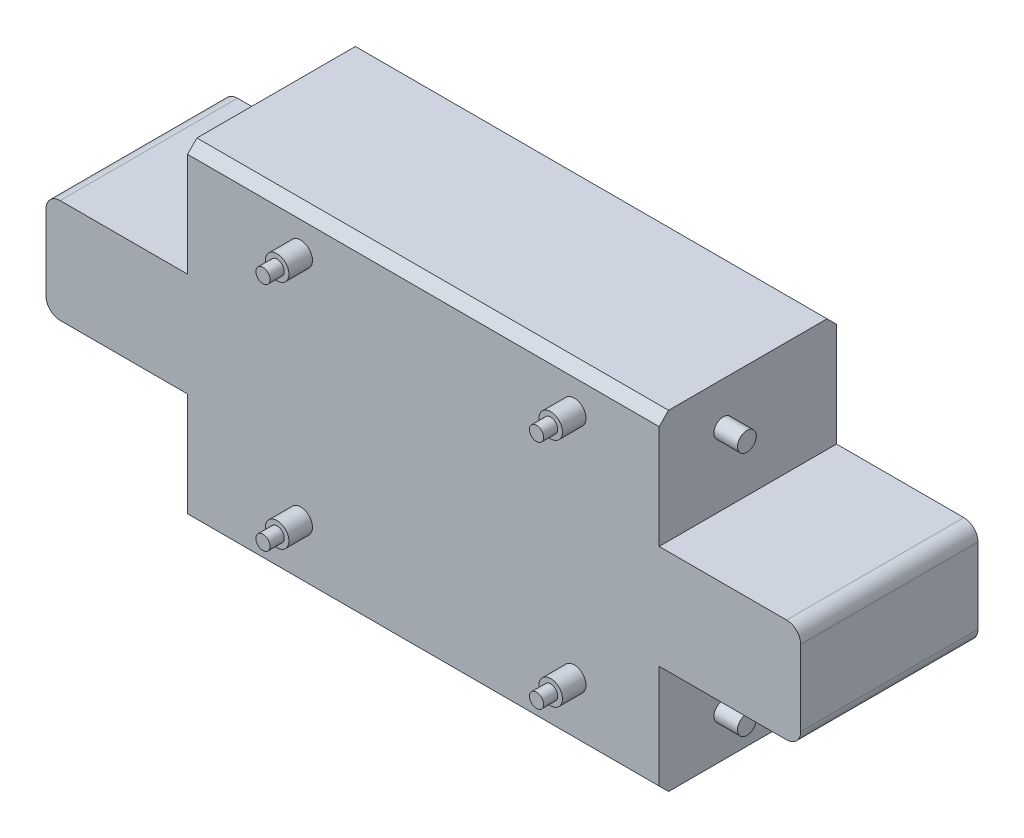
SolidWorks part; units mm, degrees
ref_plane "Alzado" through (0, 0, 0) normal (0, 0, 1) x (1, 0, 0)
ref_plane "Planta" through (0, 0, 0) normal (0, 1, 0) x (1, 0, 0)
ref_plane "Vista lateral" through (0, 0, 0) normal (1, 0, 0) x (0, 0, -1)
sketch "Croquis1" plane through (0, 0, 0) normal (0, 0, 1) x (1, 0, 0)
  line L0 (-62.5244, 0.3719) -> (-62.5244, -23.6281)
  line L5 (-62.5244, 46.3719) -> (37.4756, 46.3719)
  line L6 (-62.5244, 46.3719) -> (-62.5244, 22.3719)
  line L7 (-62.5244, -23.6281) -> (37.4756, -23.6281)
  line L8 (37.4756, 46.3719) -> (37.4756, 22.3719)
  line L9 (-62.5244, 22.3719) -> (-92.5244, 22.3719)
  line L11 (-62.5244, 0.3719) -> (-92.5244, 0.3719)
  line L12 (-92.5244, 22.3719) -> (-92.5244, 0.3719)
  line L13 (37.4756, 22.3719) -> (67.4756, 22.3719)
  line L15 (37.4756, 0.3719) -> (67.4756, 0.3719)
  line L16 (67.4756, 22.3719) -> (67.4756, 0.3719)
  line L17 (37.4756, 0.3719) -> (37.4756, -23.6281)
  point P12 (-12.5244, -23.6281)
  dimension "D1" = 160
  dimension "D2" = 22
  dimension "D3" = 70
  dimension "D4" = 24
  dimension "D5" = 24
  dimension "D6" = 22
  dimension "D7" = 100
  dimension "D8" = 80
  dimension "D9" = 30
extrude "Saliente-Extruir1" add sketch "Croquis1" along normal blind 37.6
sketch "Croquis2" plane through (-62.5244, 0, 0) normal (-1, 0, 0) x (0, 0, 1)
  line L2 (0, 0.3719) -> (0, -23.6281) construction
  line L3 (37.6, -23.6281) -> (0, -23.6281) construction
  line L4 (0, 46.3719) -> (0, 22.3719) construction
  line L5 (37.6, 46.3719) -> (0, 46.3719) construction
  circle A0 centre (24, -14.6281) radius 2
  circle A1 centre (24, 37.3719) radius 2
  dimension "D3" = 4
  dimension "D4" = 4
  dimension "D1" = 24
  dimension "D2" = 9
  dimension "D5" = 24
  dimension "D6" = 9
extrude "Saliente-Extruir2" add sketch "Croquis2" along normal blind 5 and the other way blind 105
fillet "Redondeo1" radius 3 2 edges at (67.4756, 22.3719, 18.8) (67.4756, 0.3719, 18.8)
chamfer "Chaflán1" distance 2 angle 45 2 edges at (-12.5244, -23.6281, 0) (-12.5244, 46.3719, 0)
chamfer "Chaflán2" distance 2 angle 45 2 edges at (-12.5244, -23.6281, 37.6) (-12.5244, 46.3719, 37.6)
fillet "Redondeo2" radius 3 2 edges at (-92.5244, 22.3719, 18.8) (-92.5244, 0.3719, 18.8)
sketch "Croquis3" plane through (0, 0, 37.6) normal (0, 0, 1) x (1, 0, 0)
  line L0 (67.4756, 3.3719) -> (67.4756, 19.3719) construction
  line L1 (37.4756, 44.3719) -> (-62.5244, 44.3719) construction
  circle A0 centre (-38.5244, 38.1219) radius 2.5
  circle A1 centre (19.4756, 38.1219) radius 2.5
  circle A2 centre (-38.5244, -10.8781) radius 2.5
  circle A3 centre (19.4756, -10.8781) radius 2.5
  dimension "D1" = 5
  dimension "D2" = 5
  dimension "D3" = 5
  dimension "D4" = 5
  dimension "D5" = 58
  dimension "D6" = 49
  dimension "D7" = 48
  dimension "D8" = 6.25
extrude "Saliente-Extruir3" add sketch "Croquis3" along normal blind 5
sketch "Croquis4" plane through (0, 0, 42.6) normal (0, 0, 1) x (1, 0, 0)
  circle A0 centre (-38.5244, 38.1219) radius 1.5
  circle A1 centre (19.4756, 38.1219) radius 1.5
  circle A2 centre (-38.5244, -10.8781) radius 1.5
  circle A3 centre (19.4756, -10.8781) radius 1.5
extrude "Saliente-Extruir4" add sketch "Croquis4" along normal blind 3
